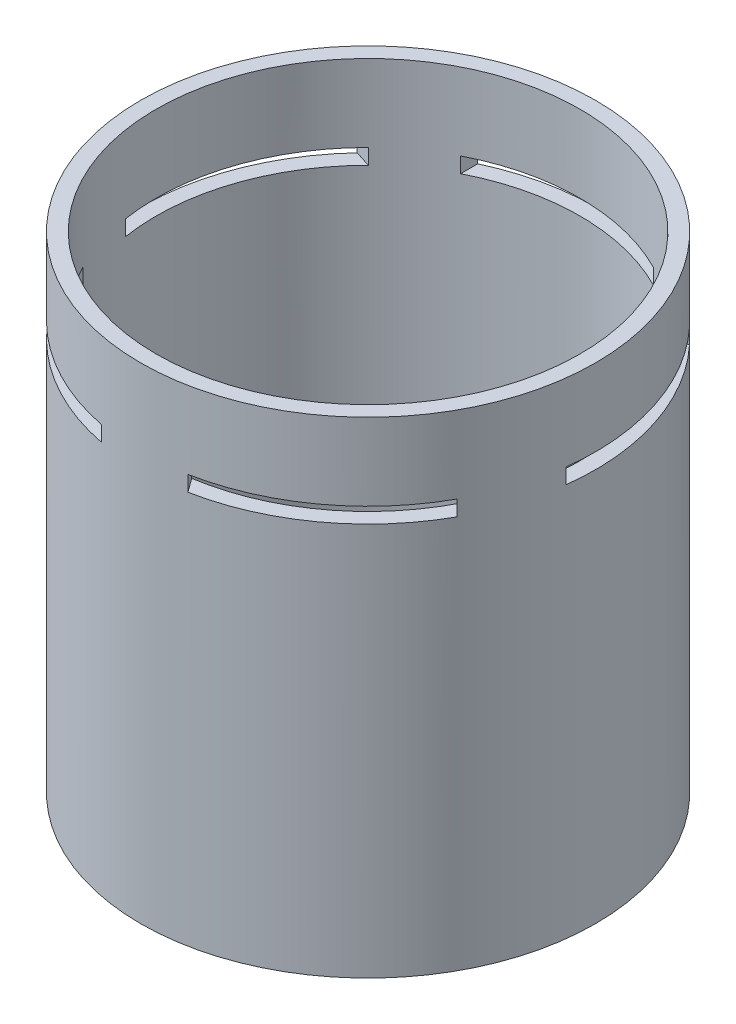
SolidWorks part; units mm, degrees
ref_plane "Front Plane" through (0, 0, 0) normal (0, 0, 1) x (1, 0, 0)
ref_plane "Top Plane" through (0, 0, 0) normal (0, 1, 0) x (1, 0, 0)
ref_plane "Right Plane" through (0, 0, 0) normal (1, 0, 0) x (0, 0, -1)
sketch "Sketch1" plane through (0, 0, 0) normal (0, 1, 0) x (1, 0, 0)
  circle A0 centre (0, 0) radius 29.5
  circle A1 centre (0, 0) radius 27.5
  dimension "D1" = 59
  dimension "D2" = 55
extrude "Boss-Extrude1" add sketch "Sketch1" along normal blind 63
sketch "Sketch3" plane through (0, 0, 0) normal (0, 0, 1) x (1, 0, 0)
  line L0 (0, 63) -> (0, 53) construction
  line L1 (29.5, 63) -> (-29.5, 63) construction
  line L2 (0, 53) -> (12.5, 53)
  line L3 (12.5, 53) -> (12.5, 51)
  line L4 (12.5, 51) -> (-12.5, 51)
  line L5 (-12.5, 51) -> (-12.5, 53)
  line L6 (-12.5, 53) -> (0, 53)
  dimension "D1" = 10
  dimension "D2" = 12.5
  dimension "D3" = 2
  dimension "D4" = 25
extrude "Cut-Extrude1" cut sketch "Sketch3" against normal blind 33
pattern_circular "CirPattern1" count 5 over 360 about axis through (0, 0, 0) along (0, 1, 0) of "Cut-Extrude1"
